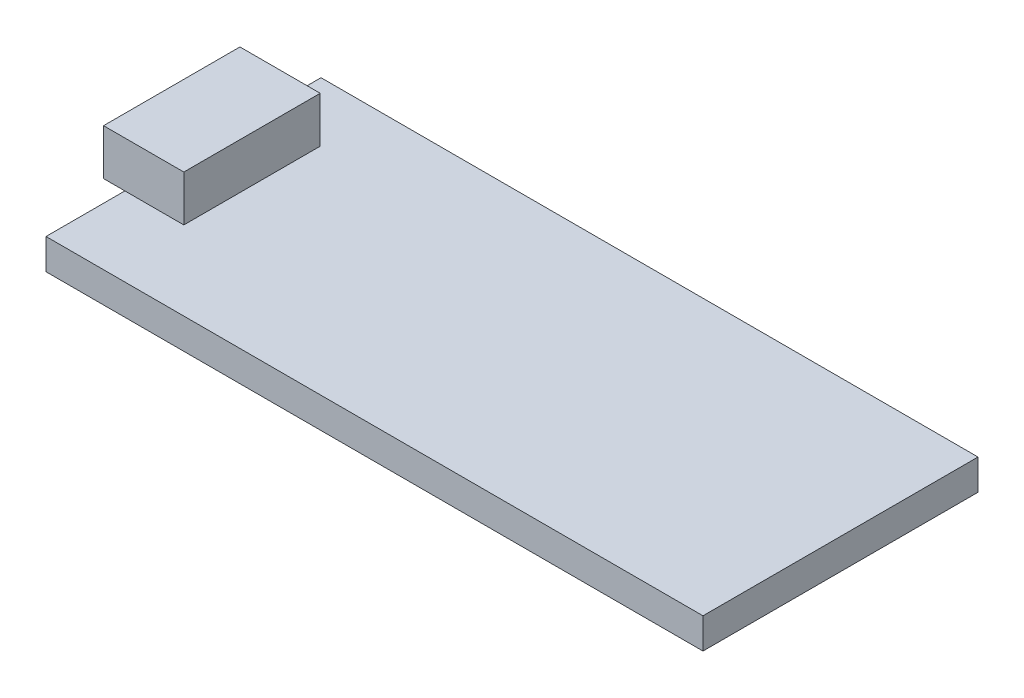
SolidWorks part; units mm, degrees
ref_plane "Front Plane" through (0, 0, 0) normal (0, 0, 1) x (1, 0, 0)
ref_plane "Top Plane" through (0, 0, 0) normal (0, 1, 0) x (1, 0, 0)
ref_plane "Right Plane" through (0, 0, 0) normal (1, 0, 0) x (0, 0, -1)
sketch "Sketch1" plane through (0, 0, 0) normal (0, 1, 0) x (1, 0, 0)
  line L1 (0, 0) -> (43, 0)
  line L2 (0, 0) -> (0, -18)
  line L3 (0, -18) -> (43, -18)
  line L4 (43, 0) -> (43, -18)
  dimension "D1" = 43
  dimension "D2" = 18
extrude "Boss-Extrude1" add sketch "Sketch1" along normal blind 2
sketch "Sketch2" plane through (0, 2, 0) normal (0, 1, 0) x (1, 0, 0)
  line L1 (-1.3974, -3.91) -> (3.8568, -3.91)
  line L2 (-1.3974, -3.91) -> (-1.3974, -12.8361)
  line L3 (-1.3974, -12.8361) -> (3.8568, -12.8361)
  line L4 (3.8568, -3.91) -> (3.8568, -12.8361)
extrude "Boss-Extrude2" add sketch "Sketch2" along normal blind 3
